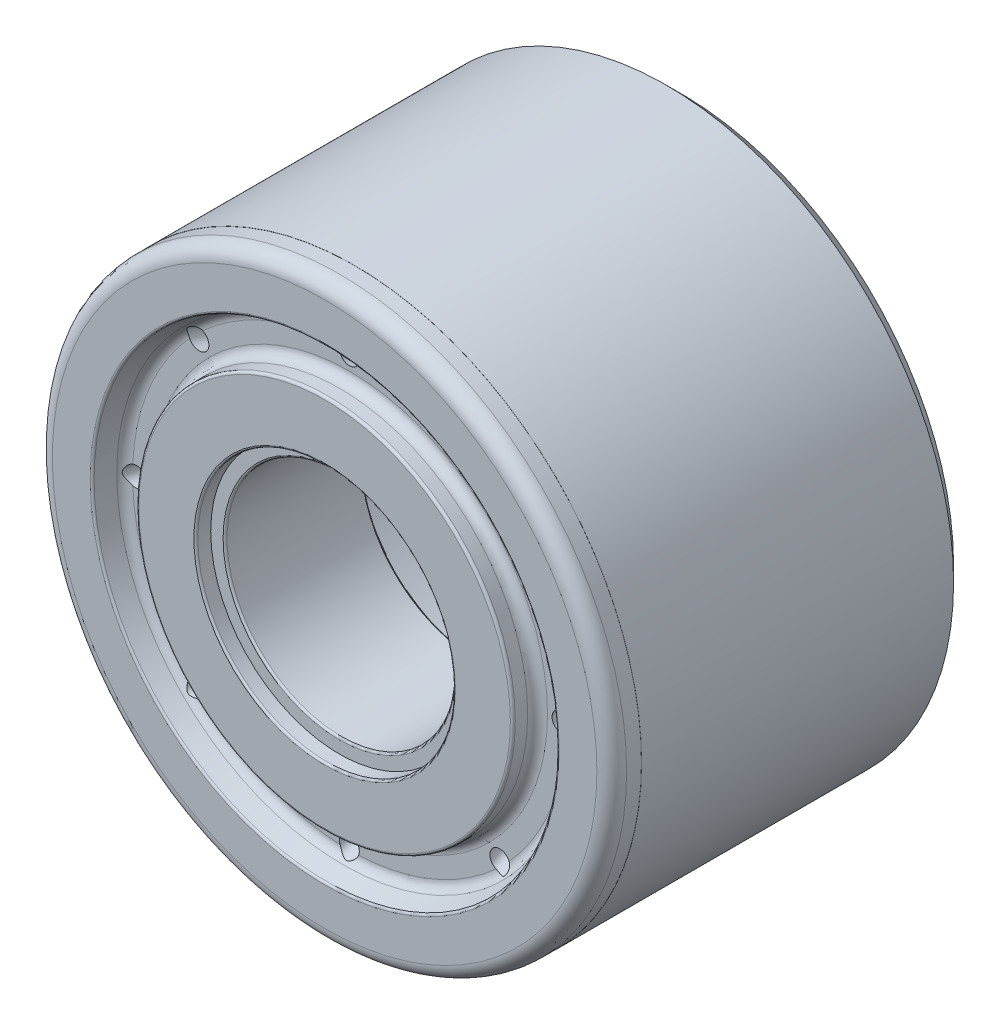
SolidWorks part; units mm, degrees
material "Phosphor bronze 10% D, UNS C52400"
ref_plane "Front Plane" through (0, 0, 0) normal (0, 0, 1) x (1, 0, 0)
ref_plane "Top Plane" through (0, 0, 0) normal (0, 1, 0) x (1, 0, 0)
ref_plane "Right Plane" through (0, 0, 0) normal (1, 0, 0) x (0, 0, -1)
sketch "Sketch1" plane through (0, 0, 0) normal (1, 0, 0) x (0, 0, -1)
  line L0 (0, 26.4) -> (0, 37.5)
  line L1 (0.5, 38) -> (3, 38)
  line L2 (5, 40) -> (5, 43.7797)
  line L3 (3.684, 45.6591) -> (0.329, 46.8803)
  line L4 (0, 47.3501) -> (0, 54.975)
  line L5 (3, 57.975) -> (6, 57.975)
  line L6 (6, 57.975) -> (6, 58)
  line L7 (6, 58) -> (69, 58)
  line L8 (72, 55) -> (72, 48)
  line L10 (36, 47.5) -> (35, 48.5)
  line L11 (35, 48.5) -> (33, 48.5)
  line L12 (31, 46.5) -> (31, 44.3)
  line L13 (31.8, 43.5) -> (32, 43.5)
  line L14 (32.5, 43) -> (32.5, 25.75)
  line L15 (32, 25.25) -> (31, 25.25)
  line L16 (31, 25.25) -> (31, 23.6029)
  line L17 (30.5, 23.1029) -> (3.4, 23.1029)
  line L18 (3, 23.5029) -> (3, 26)
  line L19 (3, 26) -> (0.4, 26)
  line L20 (69, 58) -> (72, 55)
  line L21 (31, 23.6029) -> (30.5, 23.1029)
  line L22 (0, 0) -> (88.7413, 0) construction
  line L23 (63.5, 47.5) -> (71.5, 47.5)
  line L24 (36, 47.5) -> (44.5, 47.5)
  line L25 (45.5, 47.5) -> (62.5, 47.5)
  arc A0 (72, 48) -> (71.5, 47.5) centre (71.5, 48) cw
  arc A1 (32, 43.5) -> (32.5, 43) centre (32, 43) cw
  arc A2 (32, 25.25) -> (32.5, 25.75) centre (32, 25.75) ccw
  arc A3 (31, 46.5) -> (33, 48.5) centre (33, 46.5) cw
  arc A4 (31.8, 43.5) -> (31, 44.3) centre (31.8, 44.3) cw
  arc A5 (0, 54.975) -> (3, 57.975) centre (3, 54.975) cw
  arc A6 (0.329, 46.8803) -> (0, 47.3501) centre (0.5, 47.3501) cw
  arc A7 (3.684, 45.6591) -> (5, 43.7797) centre (3, 43.7797) cw
  arc A8 (5, 40) -> (3, 38) centre (3, 40) cw
  arc A9 (0.5, 38) -> (0, 37.5) centre (0.5, 37.5) ccw
  arc A10 (0.4, 26) -> (0, 26.4) centre (0.4, 26.4) cw
  arc A11 (3.4, 23.1029) -> (3, 23.5029) centre (3.4, 23.5029) cw
  arc A14 (62.5, 47.5) -> (63.5, 47.5) centre (63, 47.5) cw
  arc A15 (44.5, 47.5) -> (45.5, 47.5) centre (45, 47.5) cw
  point P3 (31.5, 25.25)
  point P10 (72, 58)
  point P19 (31, 23.1029)
  point P38 (0, 57.975)
  point P41 (0, 47)
  point P46 (5, 38)
  point P49 (0, 38)
  point P52 (0, 26)
  dimension "D21" = 0.5
  dimension "D22" = 0.5
  dimension "D24" = 0.5
  dimension "D25" = 2
  dimension "D26" = 0.8
  dimension "D28" = 3
  dimension "D29" = 0.5
  dimension "D30" = 2
  dimension "D31" = 2
  dimension "D32" = 0.5
  dimension "D33" = 0.4
  dimension "D34" = 0.4
  dimension "D35" = 0.5
  dimension "D36" = 27
  dimension "D9" = 0.5
  dimension "D41" = 47.5
  dimension "D1" = 23.1029
  dimension "D2" = 26
  dimension "D3" = 38
  dimension "D4" = 47
  dimension "D5" = 57.975
  dimension "D6" = 58
  dimension "D7" = 25.25
  dimension "D8" = 43.5
  dimension "D10" = 48.5
  dimension "D11" = 3
  dimension "D12" = 5
  dimension "D13" = 6
  dimension "D14" = 72
  dimension "D15" = 41
  dimension "D16" = 39.5
  dimension "D17" = 41
  dimension "D18" = 37
  dimension "D19" = 36
  dimension "D20" = 70
  dimension "D37" = 9
  dimension "D38" = 47.5
  dimension "D39" = 47.5
  dimension "D40" = 47.5
  dimension "D42" = 47.5
revolve "Revolve1" add sketch "Sketch1" angle 360 about L22
sketch "Sketch2" plane through (0, 0, 0) normal (1, 0, 0) x (0, 0, -1)
  line L0 (5, 43) -> (32.5, 35.6314) construction
  line L1 (5, 43.7797) -> (5, -43.7797) construction
  line L2 (32.5, -43) -> (32.5, 43) construction
  line L3 (5, 43) -> (3.684, 45.4232)
  line L4 (3.684, 45.6591) -> (3.684, -45.6591) construction
  line L5 (3.684, 45.4232) -> (34.8794, 37.0644)
  line L6 (34.8794, 37.0644) -> (32.5, 35.6314)
  line L7 (0, 0) -> (51.7355, 0) construction
  line L8 (5, 43) -> (32.5, 35.6314)
  dimension "D1" = 4
  dimension "D2" = 43
  dimension "D3" = 15
revolve "Cut-Revolve1" cut sketch "Sketch2" angle 360 about L8
pattern_circular "CirPattern1" count 8 over 360 about axis through (0, 0, 0) along (0, 0, 1) of "Cut-Revolve1"
sketch "Sketch4" plane through (0, 0, 0) normal (1, 0, 0) x (0, 0, -1)
  line L0 (35, 27) -> (35, 44) construction
  line L2 (35, 44) -> (31, 44)
  line L3 (31, 44) -> (31, 31)
  line L4 (32.5, -43) -> (32.5, 43) construction
  line L5 (35, 27) -> (35, 44)
  arc A0 (31, 31) -> (35, 27) centre (35, 31) ccw
  dimension "D1" = 4
  dimension "D2" = 31
  dimension "D3" = 1.5
  dimension "D4" = 13
revolve "Cut-Revolve2" cut sketch "Sketch4" angle 360 about L0
pattern_circular "CirPattern2" count 4 over 360 about axis through (0, 0, 0) along (0, 0, 1) of "Cut-Revolve2"
ref_plane "Plane1" through (0, 0, 0) normal (-0.7071, 0.7071, 0) x (0, 0, 1)
sketch "Sketch7" plane through (0, 0, 0) normal (-0.7071, 0.7071, 0) x (0, 0, 1)
  line L0 (-35, 41.5) -> (-35, 24.5)
  line L1 (-35, 24.5) -> (-31, 24.5)
  line L4 (-31, 24.5) -> (-31, 37.5)
  line L5 (-32.5, 24.1283) -> (-32.5, 32.5333) construction
  line L6 (-56.8604, 0) -> (18.3208, 0) construction
  arc A0 (-31, 37.5) -> (-35, 41.5) centre (-35, 37.5) ccw
  dimension "D1" = 4
  dimension "D2" = 13
  dimension "D3" = 4
  dimension "D4" = 1.5
  dimension "D5" = 37.5
revolve "Cut-Revolve4" cut sketch "Sketch7" angle 360 about L0
pattern_circular "CirPattern4" count 4 over 360 about axis through (0, 0, 0) along (0, 0, 1) of "Cut-Revolve4"
ref_plane "Plane2" through (0, 0, 0) normal (0.3827, 0.9239, 0) x (0, 0, 1)
sketch "Sketch9" plane through (0, 0, 0) normal (0.3827, 0.9239, 0) x (0, 0, 1)
  line L0 (-98.6531, 0) -> (-17.1938, 0) construction
  line L3 (-32.5, 43) -> (-32.5, 19.2968) construction
  line L4 (-34, 40) -> (-34, 36)
  arc A0 (-34, 36) -> (-34, 40) centre (-34, 38) ccw
  dimension "D1" = 4
  dimension "D3" = 1.5
  dimension "D2" = 38
revolve "Cut-Revolve5" cut sketch "Sketch9" angle 360 about L4
pattern_circular "CirPattern5" count 4 over 360 about axis through (0, 0, 0) along (0, 0, 1) of "Cut-Revolve5"
